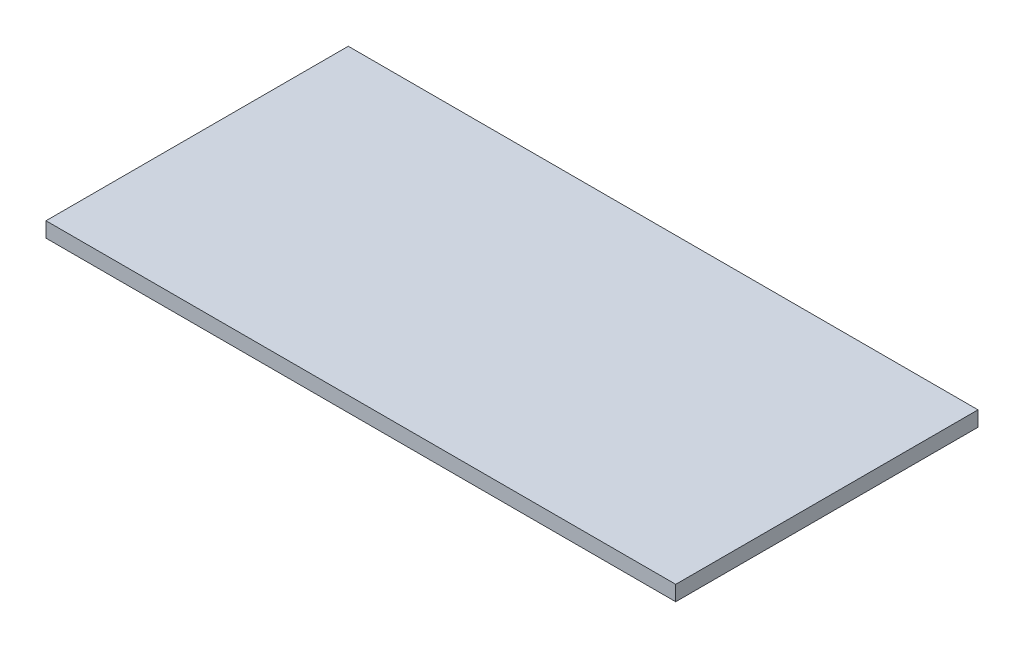
SolidWorks part; units mm, degrees
material "Сталь 3 ГОСТ 535-88"
ref_plane "Спереди" through (0, 0, 0) normal (0, 0, 1) x (1, 0, 0)
ref_plane "Сверху" through (0, 0, 0) normal (0, 1, 0) x (1, 0, 0)
ref_plane "Справа" through (0, 0, 0) normal (1, 0, 0) x (0, 0, -1)
sketch "Эскиз1" plane through (0, 0, 0) normal (0, 1, 0) x (1, 0, 0)
  line L1 (-125, 60) -> (125, 60)
  line L2 (-125, 60) -> (-125, -60)
  line L3 (-125, -60) -> (125, -60)
  line L4 (125, 60) -> (125, -60)
  line L5 (0, -60) -> (0, 60) construction
  line L6 (-125, 0) -> (125, 0) construction
  point P0 (0, 0)
  dimension "D1" = 120
  dimension "D2" = 250
extrude "Бобышка-Вытянуть1" add sketch "Эскиз1" along normal blind 6
